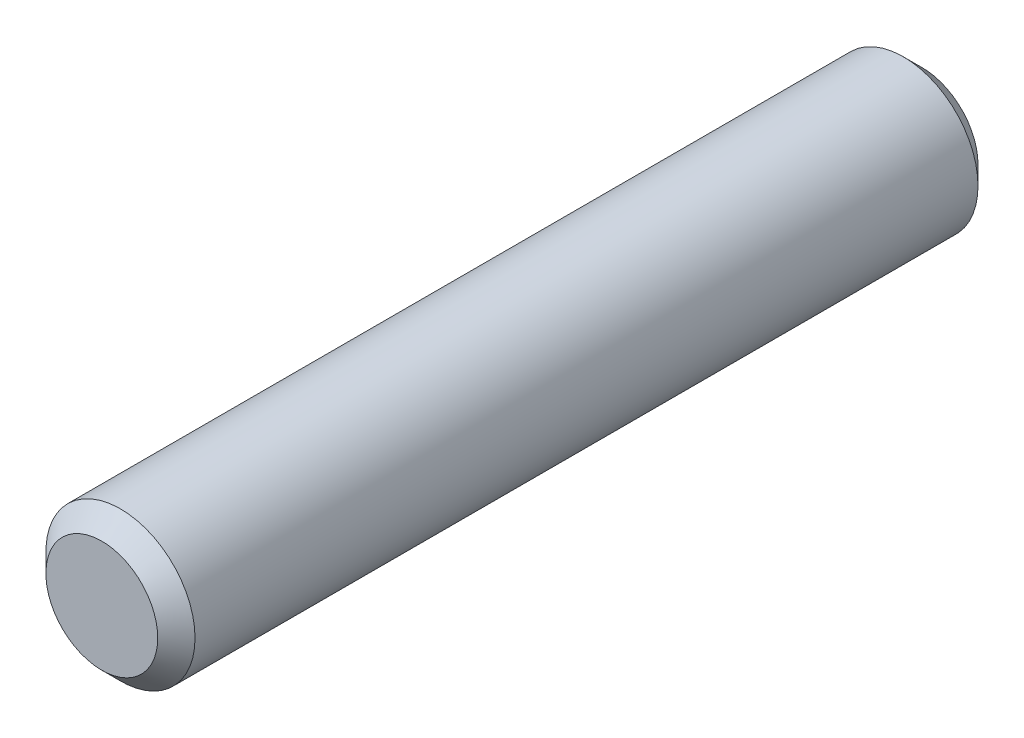
SolidWorks part; units mm, degrees
material "AISI 304"
ref_plane "Front Plane" through (0, 0, 0) normal (0, 0, 1) x (1, 0, 0)
ref_plane "Top Plane" through (0, 0, 0) normal (0, 1, 0) x (1, 0, 0)
ref_plane "Right Plane" through (0, 0, 0) normal (1, 0, 0) x (0, 0, -1)
sketch "Sketch1" plane through (0, 0, 0) normal (0, 0, 1) x (1, 0, 0)
  circle A0 centre (0, 0) radius 2
  dimension "D1" = 4
extrude "Boss-Extrude1" add sketch "Sketch1" along normal blind 22
chamfer "Chamfer1" distance 0.5 angle 45 2 edges at (2, 0, 0) (2, 0, 22)
